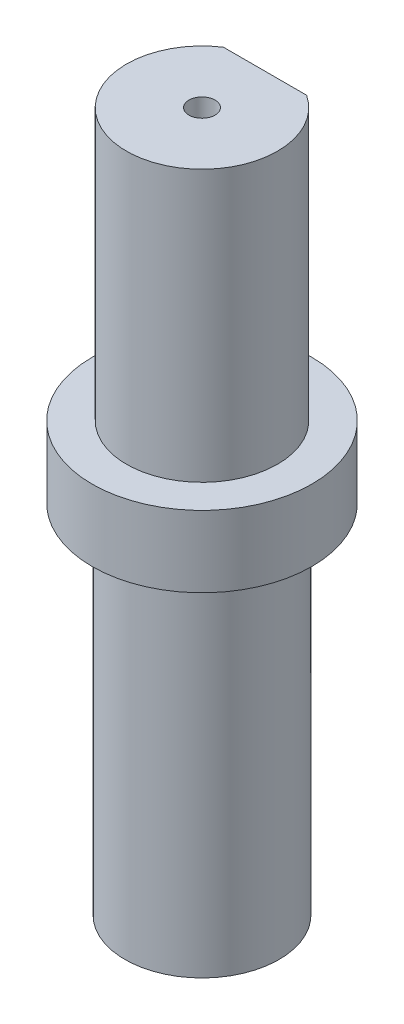
SolidWorks part; units mm, degrees
ref_plane "Front Plane" through (0, 0, 0) normal (0, 0, 1) x (1, 0, 0)
ref_plane "Top Plane" through (0, 0, 0) normal (0, 1, 0) x (1, 0, 0)
ref_plane "Right Plane" through (0, 0, 0) normal (1, 0, 0) x (0, 0, -1)
sketch "Sketch1" plane through (0, 0, 0) normal (0, 0, 1) x (1, 0, 0)
  line L0 (0, -200) -> (0, 100) construction
  line L1 (2.665, -18) -> (2.665, -5)
  line L2 (2.665, -5) -> (0.55, -5)
  line L3 (0.55, -5) -> (0.55, 11.4)
  line L4 (0.55, 11.4) -> (3.175, 11.4)
  line L5 (3.175, 11.4) -> (3.175, 0)
  line L6 (3.175, 0) -> (4.619, 0)
  line L7 (4.619, 0) -> (4.619, -3)
  line L8 (4.619, -3) -> (3.24, -3)
  line L9 (3.24, -3) -> (3.24, -18)
  line L10 (3.24, -18) -> (2.665, -18)
revolve "Revolve1" add sketch "Sketch1" angle 360 about L0
sketch "Sketch2" plane through (0, 0, 0) normal (0, 0, 1) x (1, 0, 0)
  line L0 (-4, 0) -> (4, 0)
  line L1 (4, 0) -> (4, 11.4)
  line L2 (4, 11.4) -> (-4, 11.4)
  line L3 (-4, 11.4) -> (-4, 0)
extrude "Packaging flat at Z minus2p65" cut sketch "Sketch2" against normal blind 20 from offset 2.65
